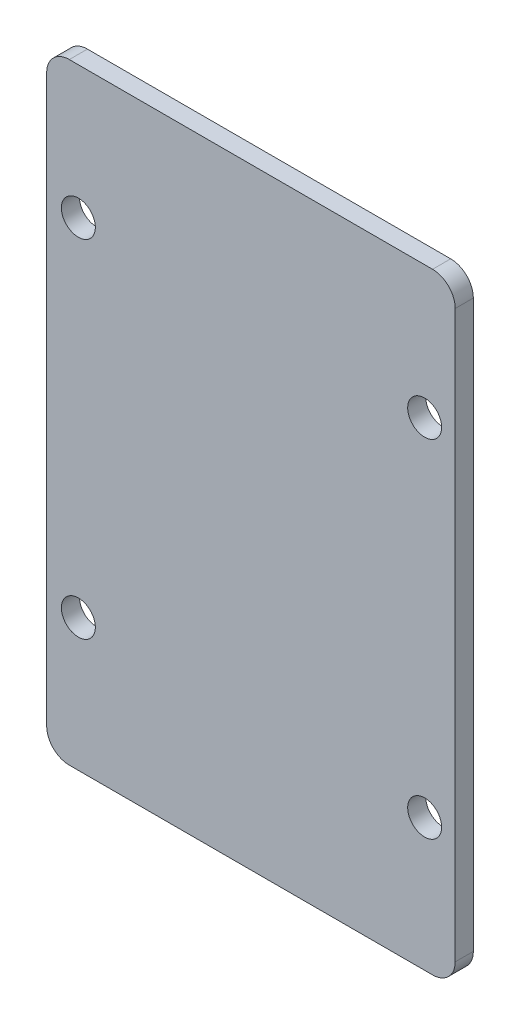
SolidWorks part; units mm, degrees
ref_plane "Front Plane" through (0, 0, 0) normal (0, 0, 1) x (1, 0, 0)
ref_plane "Top Plane" through (0, 0, 0) normal (0, 1, 0) x (1, 0, 0)
ref_plane "Right Plane" through (0, 0, 0) normal (1, 0, 0) x (0, 0, -1)
sketch "Board1"
  dimension "D3" = 2
  dimension "D1" = 54
  dimension "D2" = 36.1
  dimension "D6" = 30.6
  dimension "D7" = 30.6
  dimension "D8" = 30.6
  dimension "D10" = 2.7
  dimension "D9" = 3
  dimension "D4" = 11.7
  dimension "D5" = 30.6
sketch "Board2" plane through (0, 0, 0) normal (0, 0, 1) x (1, 0, 0)
  line L0 (115.6499, 52) -> (115.6499, 2)
  line L1 (117.6499, 0) -> (149.7499, 0)
  line L2 (151.7499, 2) -> (151.7499, 52)
  line L3 (149.7499, 54) -> (117.6499, 54)
  arc A0 (149.7499, 0) -> (151.7499, 2) centre (149.7499, 2) ccw
  arc A1 (115.6499, 2) -> (117.6499, 0) centre (117.6499, 2) ccw
  arc A2 (115.6499, 52) -> (117.6499, 54) centre (117.6499, 52) cw
  arc A3 (151.7499, 52) -> (149.7499, 54) centre (149.7499, 52) ccw
  circle A4 centre (149.0499, 42.3) radius 1.5
  circle A5 centre (149.0499, 11.7) radius 1.5
  circle A6 centre (118.4499, 11.7) radius 1.5
  circle A7 centre (118.4499, 42.3) radius 1.5
  point P7 (151.7499, 0)
  point P12 (115.6499, 54)
  point P15 (151.7499, 54)
  dimension "D3" = 2
  dimension "D6" = 30.6
  dimension "D7" = 30.6
  dimension "D5" = 30.6
  dimension "D4" = 3
  dimension "D1" = 36.1
  dimension "D2" = 54
  dimension "D8" = 2.7
  dimension "D9" = 11.7
sketch "Board3" plane through (0, 0, 0) normal (0, 0, 1) x (1, 0, 0)
  line L0 (12.8709, 54) -> (44.9709, 54)
  line L1 (46.9709, 52) -> (46.9709, 49.7006)
  line L2 (45.9709, 48.7006) -> (39.9314, 48.7006)
  line L3 (38.9314, 47.7006) -> (38.9314, 46.5412)
  line L4 (39.9314, 45.5412) -> (45.9709, 45.5412)
  line L5 (46.9709, 44.5412) -> (46.9709, 40.1406)
  line L6 (45.9709, 39.1406) -> (39.7286, 39.1406)
  line L7 (38.7286, 38.1406) -> (38.7286, 16.0292)
  line L8 (39.7286, 15.0292) -> (45.9709, 15.0292)
  line L9 (46.9709, 14.0292) -> (46.9709, 10.4124)
  line L10 (44.9709, 8.4124) -> (12.8709, 8.4124)
  line L11 (10.8709, 10.4124) -> (10.8709, 21.9198)
  line L12 (11.8709, 22.9198) -> (15.0232, 22.9198)
  line L13 (16.0232, 23.9198) -> (16.0232, 38.1107)
  line L14 (15.0232, 39.1107) -> (11.8709, 39.1107)
  line L15 (10.8709, 40.1107) -> (10.8709, 52)
  arc A0 (44.9709, 54) -> (46.9709, 52) centre (44.9709, 52) cw
  arc A1 (46.9709, 10.4124) -> (44.9709, 8.4124) centre (44.9709, 10.4124) cw
  arc A2 (12.8709, 8.4124) -> (10.8709, 10.4124) centre (12.8709, 10.4124) cw
  arc A3 (12.8709, 54) -> (10.8709, 52) centre (12.8709, 52) ccw
  arc A4 (46.9709, 49.7006) -> (45.9709, 48.7006) centre (45.9709, 49.7006) cw
  arc A5 (39.9314, 48.7006) -> (38.9314, 47.7006) centre (39.9314, 47.7006) ccw
  arc A6 (38.9314, 46.5412) -> (39.9314, 45.5412) centre (39.9314, 46.5412) ccw
  arc A7 (45.9709, 45.5412) -> (46.9709, 44.5412) centre (45.9709, 44.5412) cw
  arc A8 (46.9709, 40.1406) -> (45.9709, 39.1406) centre (45.9709, 40.1406) cw
  arc A9 (39.7286, 39.1406) -> (38.7286, 38.1406) centre (39.7286, 38.1406) ccw
  arc A10 (38.7286, 16.0292) -> (39.7286, 15.0292) centre (39.7286, 16.0292) ccw
  arc A11 (45.9709, 15.0292) -> (46.9709, 14.0292) centre (45.9709, 14.0292) cw
  arc A12 (10.8709, 21.9198) -> (11.8709, 22.9198) centre (11.8709, 21.9198) cw
  arc A13 (15.0232, 22.9198) -> (16.0232, 23.9198) centre (15.0232, 23.9198) ccw
  arc A14 (16.0232, 38.1107) -> (15.0232, 39.1107) centre (15.0232, 38.1107) ccw
  arc A15 (11.8709, 39.1107) -> (10.8709, 40.1107) centre (11.8709, 40.1107) cw
  circle A16 centre (13.6709, 42.3) radius 1.5
  circle A17 centre (44.2709, 42.3) radius 1.5
  circle A18 centre (13.6709, 11.7) radius 1.5
  circle A19 centre (44.2709, 11.7) radius 1.5
  dimension "D3" = 2
  dimension "D4" = 1
  dimension "D5" = 3
  dimension "D1" = 54
  dimension "D2" = 36.1
  dimension "D6" = 30.6
  dimension "D7" = 30.6
  dimension "D9" = 30.6
  dimension "D8" = 30.6
  dimension "D10" = 2.7
  dimension "D11" = 11.7
extrude "Бобышка-Вытянуть2" add sketch "Board2" along normal blind 1.6
equation "\"D7@Board3\" = \"D6@Board3\""
equation "\"D9@Board3\" = \"D6@Board3\""
equation "\"D8@Board3\" = \"D6@Board3\""
equation "\"D8@Board1\"=\"D6@Board1\""
equation "\"D5@Board1\"=\"D6@Board1\""
equation "\"D7@Board1\"=\"D6@Board1\""
equation "\"D6@Board2\"=\"D5@Board2\""
equation "\"D7@Board2\"=\"D5@Board2\""
